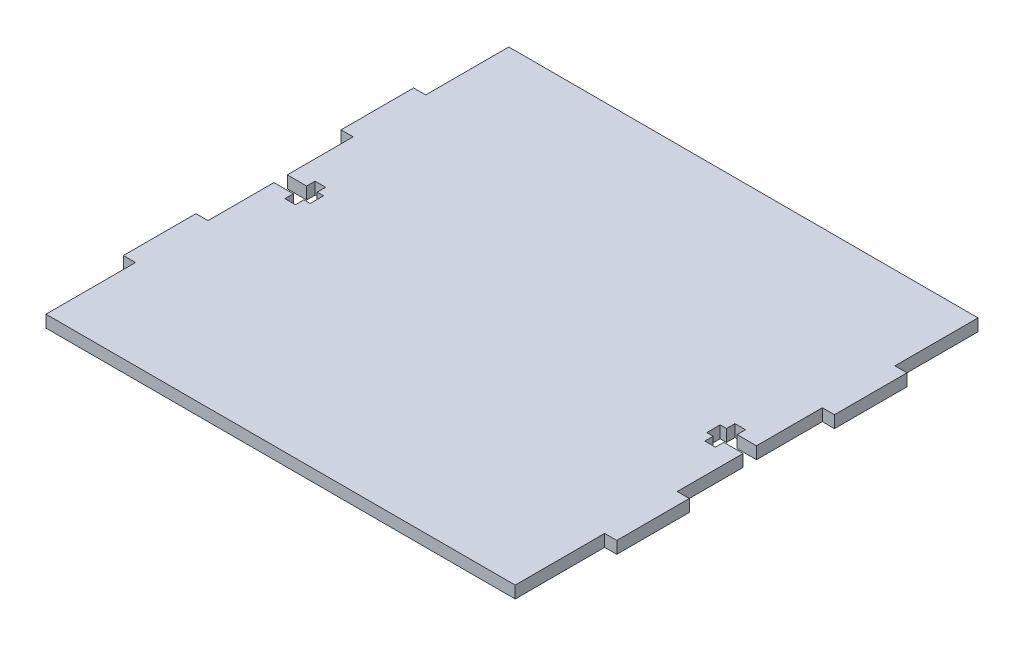
SolidWorks part; units mm, degrees
ref_plane "Front Plane" through (0, 0, 0) normal (0, 0, 1) x (1, 0, 0)
ref_plane "Top Plane" through (0, 0, 0) normal (0, 1, 0) x (1, 0, 0)
ref_plane "Right Plane" through (0, 0, 0) normal (1, 0, 0) x (0, 0, -1)
sketch "Sketch1" plane through (0, 0, 0) normal (0, 1, 0) x (1, 0, 0)
  line L0 (0, 99.695) -> (0, 121.5123)
  line L1 (0, 0) -> (123.19, 0)
  line L2 (0, 0) -> (0, 23.495)
  line L3 (0, 121.5123) -> (123.19, 121.5123)
  line L4 (123.19, 0) -> (123.19, 23.495)
  line L5 (0, 99.695) -> (-3.175, 99.695)
  line L6 (115.3319, 59.8424) -> (115.3319, 57.6262)
  line L7 (0, 80.645) -> (-3.175, 80.645)
  line L8 (-3.175, 99.695) -> (-3.175, 80.645)
  line L9 (0, 42.545) -> (-3.175, 42.545)
  line L10 (123.19, 42.545) -> (123.19, 59.8424)
  line L11 (0, 23.495) -> (-3.175, 23.495)
  line L12 (-3.175, 42.545) -> (-3.175, 23.495)
  line L13 (123.19, 99.695) -> (126.365, 99.695)
  line L15 (123.19, 80.645) -> (126.365, 80.645)
  line L16 (126.365, 99.695) -> (126.365, 80.645)
  line L17 (123.19, 42.545) -> (126.365, 42.545)
  line L18 (123.19, 99.695) -> (123.19, 121.5123)
  line L19 (123.19, 23.495) -> (126.365, 23.495)
  line L20 (126.365, 42.545) -> (126.365, 23.495)
  line L21 (123.19, 63.3476) -> (123.19, 59.8424) construction
  line L24 (118.11, 63.3476) -> (123.19, 63.3476)
  line L25 (118.11, 59.8424) -> (123.19, 59.8424)
  line L26 (123.19, 61.595) -> (113.665, 61.595) construction
  line L27 (115.3319, 65.5637) -> (118.11, 65.5637)
  line L28 (115.3319, 65.5637) -> (115.3319, 63.3476)
  line L29 (115.3319, 57.6262) -> (118.11, 57.6262)
  line L30 (118.11, 65.5637) -> (118.11, 63.3476)
  line L31 (113.665, 63.3476) -> (115.3319, 63.3476)
  line L32 (113.665, 63.3476) -> (113.665, 59.8424)
  line L33 (113.665, 59.8424) -> (115.3319, 59.8424)
  line L34 (118.11, 59.8424) -> (118.11, 57.6262)
  line L36 (123.19, 63.3476) -> (123.19, 80.645)
  line L37 (7.8581, 65.5637) -> (5.08, 65.5637)
  line L38 (5.08, 57.6263) -> (5.08, 59.8424)
  line L41 (0, 80.645) -> (0, 63.3476)
  line L42 (9.525, 59.8424) -> (7.8581, 59.8424)
  line L43 (7.8581, 63.3476) -> (7.8581, 65.5637)
  line L44 (9.525, 63.3476) -> (7.8581, 63.3476)
  line L45 (0, 59.8424) -> (0, 42.545)
  line L46 (0, 61.595) -> (9.525, 61.595) construction
  line L49 (7.8581, 57.6263) -> (5.08, 57.6263)
  line L50 (5.08, 63.3476) -> (0, 63.3476)
  line L52 (5.08, 63.3476) -> (5.08, 65.5637)
  line L53 (7.8581, 57.6263) -> (7.8581, 59.8424)
  line L54 (0, 59.8424) -> (0, 63.3476) construction
  line L55 (9.525, 59.8424) -> (9.525, 63.3476)
  line L56 (5.08, 59.8424) -> (0, 59.8424)
  dimension "D1" = 19.05
  dimension "D2" = 123.19
  dimension "D3" = 121.5123
  dimension "D4" = 21.8173
  dimension "D5" = 5.08
  dimension "D6" = 3.5052
  dimension "D7" = 23.495
  dimension "D8" = 7.9375
  dimension "D9" = 9.525
  dimension "D10" = 3.175
  dimension "D11" = 5.08
  dimension "D12" = 2.7781
  dimension "D15" = 3.5052
  dimension "D16" = 7.9375
  dimension "D17" = 9.525
  dimension "D20" = 2.7781
extrude "Boss-Extrude1" add sketch "Sketch1" along normal blind 3.175
